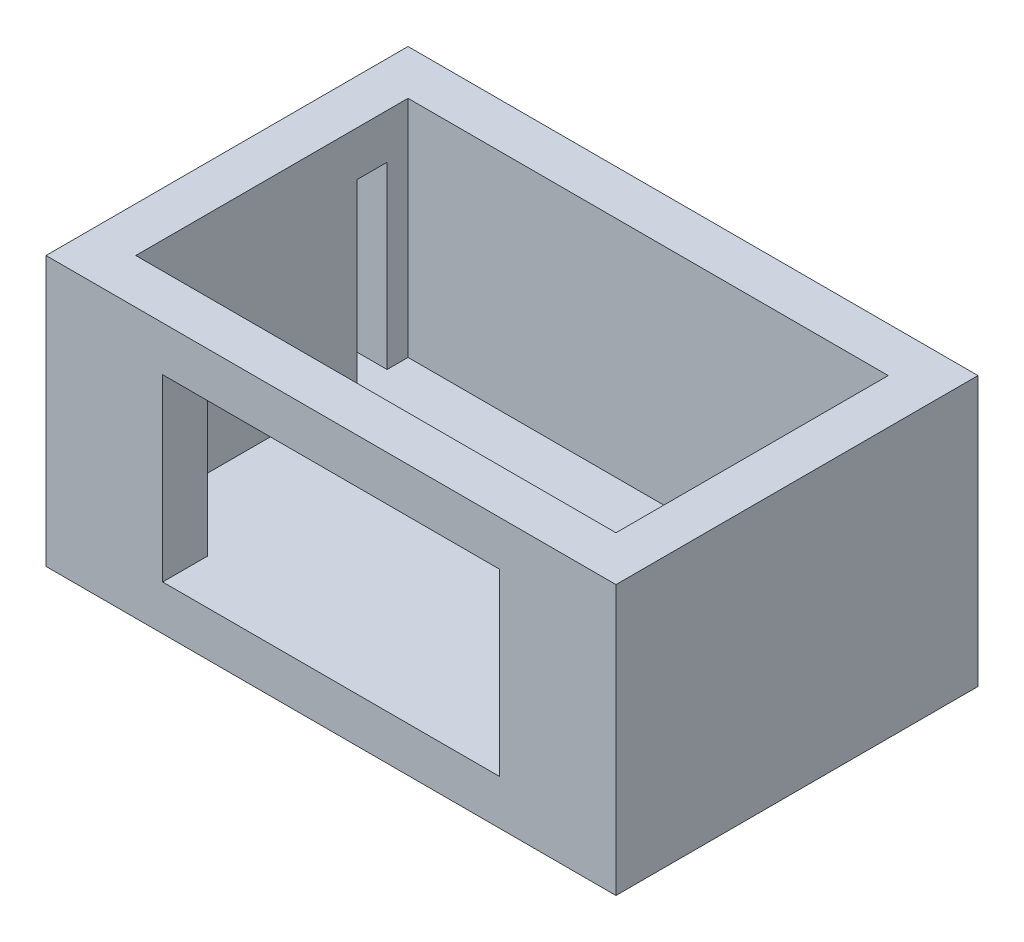
SolidWorks part; units mm, degrees
ref_plane "Front Plane" through (0, 0, 0) normal (0, 0, 1) x (1, 0, 0)
ref_plane "Top Plane" through (0, 0, 0) normal (0, 1, 0) x (1, 0, 0)
ref_plane "Right Plane" through (0, 0, 0) normal (1, 0, 0) x (0, 0, -1)
sketch "Sketch1" plane through (0, 0, 0) normal (0, 1, 0) x (1, 0, 0)
  line L1 (-37.6641, 26.7994) -> (0.4359, 26.7994)
  line L2 (-37.6641, 26.7994) -> (-37.6641, 2.5994)
  line L3 (-37.6641, 2.5994) -> (0.4359, 2.5994)
  line L4 (0.4359, 26.7994) -> (0.4359, 2.5994)
  dimension "D1" = 24.2
  dimension "D2" = 38.1
extrude "Boss-Extrude1" add sketch "Sketch1" along normal blind 18
shell "Shell1" thickness 3
sketch "Sketch2" plane through (0, 0, -2.5994) normal (0, 0, 1) x (1, 0, 0)
  line L0 (-37.6641, 18) -> (0.4359, 18) construction
  line L1 (-29.8641, 15) -> (-7.3641, 15)
  line L2 (-29.8641, 15) -> (-29.8641, 3)
  line L3 (-29.8641, 3) -> (-7.3641, 3)
  line L4 (-7.3641, 15) -> (-7.3641, 3)
  line L5 (-37.6641, 18) -> (-37.6641, 0) construction
  dimension "D1" = 12
  dimension "D2" = 22.5
  dimension "D3" = 3
  dimension "D4" = 7.8
extrude "Cut-Extrude1" cut sketch "Sketch2" against normal blind 3 contours L2 L1 L4 L3
sketch "Sketch3" plane through (-37.6641, 0, 0) normal (-1, 0, 0) x (0, 0, 1)
  line L0 (-26.7994, 18) -> (-26.7994, 0) construction
  line L1 (-22.3994, 15) -> (-20.3994, 15)
  line L2 (-22.3994, 15) -> (-22.3994, 3)
  line L3 (-22.3994, 3) -> (-20.3994, 3)
  line L4 (-20.3994, 15) -> (-20.3994, 3)
  line L5 (-26.7994, 18) -> (-2.5994, 18) construction
  dimension "D1" = 12
  dimension "D2" = 2
  dimension "D3" = 4.4
  dimension "D4" = 3
extrude "Cut-Extrude2" cut sketch "Sketch3" against normal blind 3 contours L2 L1 L4 L3
